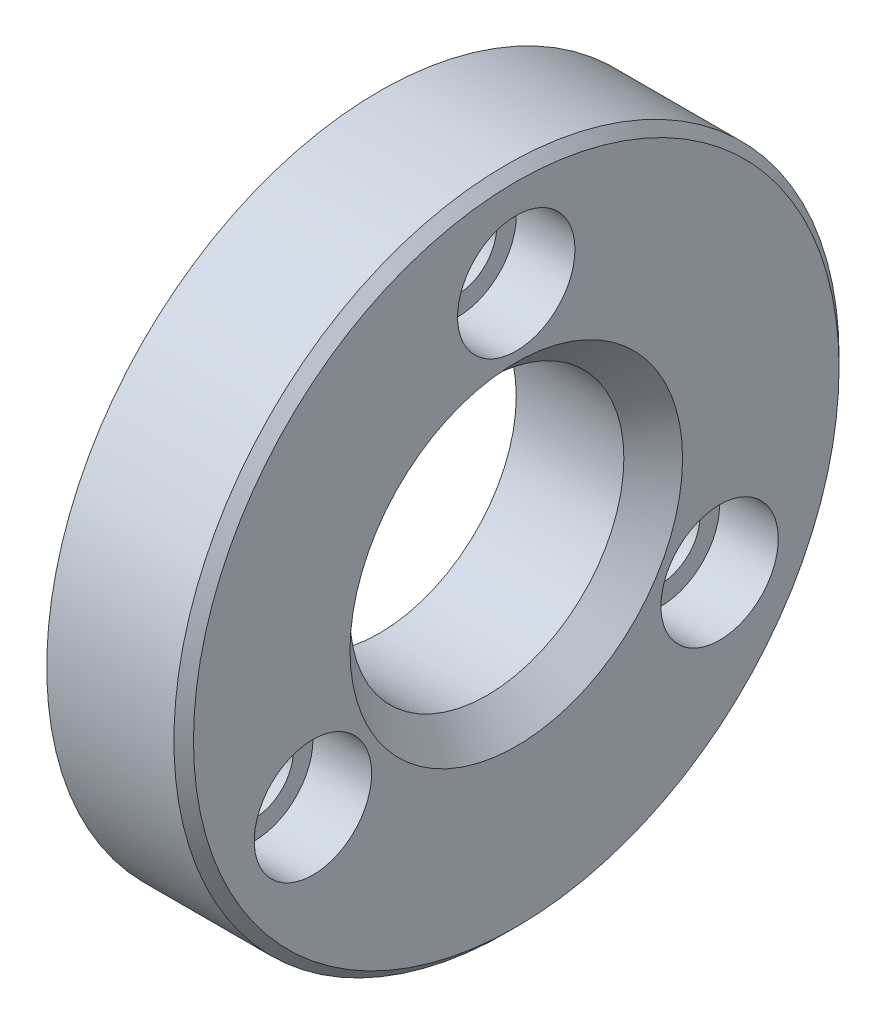
SolidWorks part; units mm, degrees
material "灰铸铁"
ref_plane "前视基准面" through (0, 0, 0) normal (0, 0, 1) x (1, 0, 0)
ref_plane "上视基准面" through (0, 0, 0) normal (0, 1, 0) x (1, 0, 0)
ref_plane "右视基准面" through (0, 0, 0) normal (1, 0, 0) x (0, 0, -1)
sketch "草图1" plane through (0, 0, 0) normal (1, 0, 0) x (0, 0, -1)
  line L0 (0, 0) -> (0, 19.8989) construction
  circle A0 centre (0, 0) radius 17
  circle A1 centre (0, 0) radius 12 construction
  circle A2 centre (0, 0) radius 7
  circle A3 centre (0, 12) radius 2
  circle A4 centre (10.3923, -6) radius 2
  circle A5 centre (-10.3923, -6) radius 2
  point P15 (0, 0)
  dimension "D1" = 14
  dimension "D2" = 24
  dimension "D3" = 34
  dimension "D4" = 4
  dimension "D5" = 3
extrude "凸台-拉伸1" add sketch "草图1" along normal blind 7
sketch "草图2" plane through (7, 0, 0) normal (1, 0, 0) x (0, 0, -1)
  circle A0 centre (0, 12) radius 3
  circle A1 centre (10.3923, -6) radius 3
  circle A2 centre (-10.3923, -6) radius 3
  point P10 (0, 0)
  dimension "D1" = 6
  dimension "D2" = 3
extrude "切除-拉伸1" cut sketch "草图2" against normal blind 3
chamfer "倒角1" distance 1.5 angle 45 1 edges at (7, 0, -7)
chamfer "倒角2" distance 0.5 angle 45 1 edges at (7, 0, -17)
